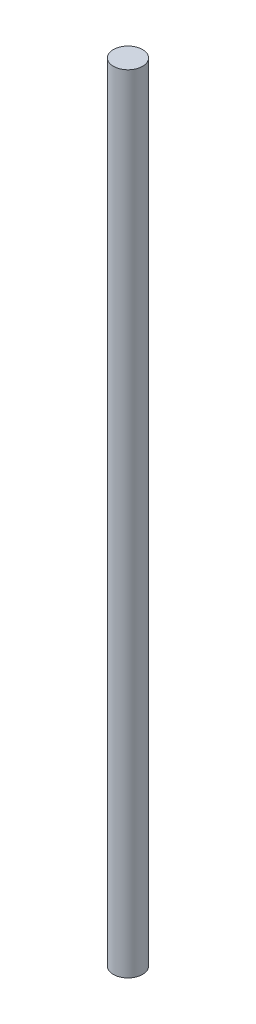
SolidWorks part; units mm, degrees
material "Brass"
ref_plane "Plan de face" through (0, 0, 0) normal (0, 0, 1) x (1, 0, 0)
ref_plane "Plan de dessus" through (0, 0, 0) normal (0, 1, 0) x (1, 0, 0)
ref_plane "Plan de droite" through (0, 0, 0) normal (1, 0, 0) x (0, 0, -1)
sketch "Sketch1" plane through (0, 0, 0) normal (0, 1, 0) x (1, 0, 0)
  circle A0 centre (0, 0) radius 1
  dimension "D1" = 2
extrude "Boss-Extrude1" add sketch "Sketch1" along normal blind 54
